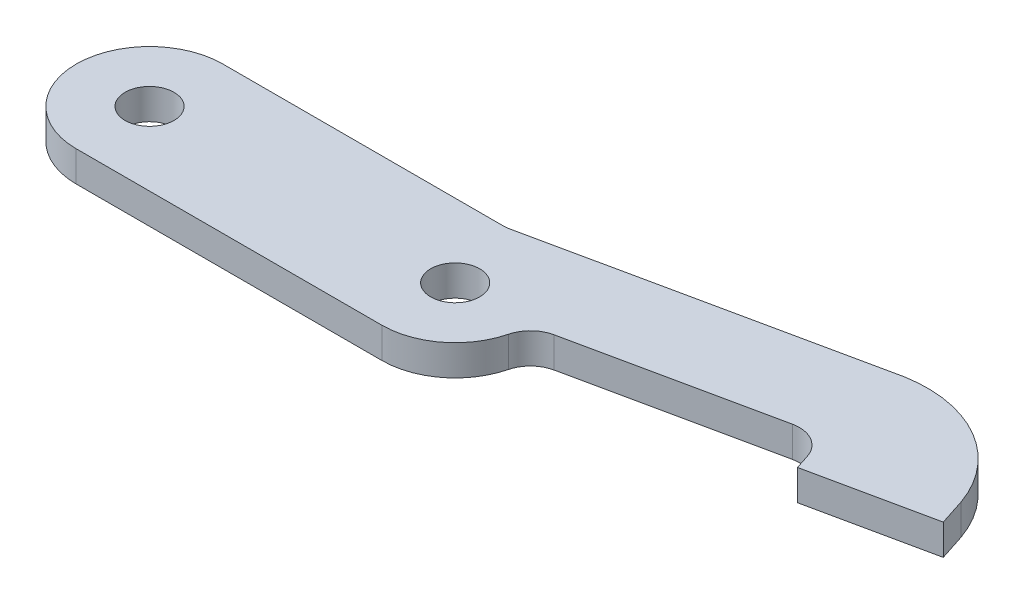
SolidWorks part; units mm, degrees
ref_plane "Front Plane" through (0, 0, 0) normal (0, 0, 1) x (1, 0, 0)
ref_plane "Top Plane" through (0, 0, 0) normal (0, 1, 0) x (1, 0, 0)
ref_plane "Right Plane" through (0, 0, 0) normal (1, 0, 0) x (0, 0, -1)
sketch "Sketch1" plane through (0, 0, 0) normal (0, 1, 0) x (1, 0, 0)
  line L0 (0, 12) -> (46.3095, 12)
  line L3 (0, -12) -> (50, -12)
  line L4 (62, 0) -> (102, 8.5023)
  line L5 (46.3095, 12) -> (100.1077, 23.4351)
  line L6 (122.4396, 10.3048) -> (123.8266, 6.0238)
  line L7 (146.0527, 1.8431) -> (104.1576, 1.8431) construction
  line L8 (104.1576, 1.8431) -> (102, 8.5023)
  line L9 (50, 0) -> (91.7136, 0) construction
  line L10 (104.1576, 1.8431) -> (123.8266, 6.0238)
  circle A0 centre (0, 0) radius 4
  circle A1 centre (50, 0) radius 4
  arc A2 (0, 12) -> (0, -12) centre (0, 0) ccw
  arc A3 (50, -12) -> (62, 0) centre (50, 0) ccw
  arc A5 (122.4396, 10.3048) -> (100.1077, 23.4351) centre (103.5499, 3.7336) ccw
  dimension "D1" = 8
  dimension "D2" = 24
  dimension "D10" = 20
  dimension "D3" = 50
  dimension "D4" = 15
  dimension "D5" = 4.5
  dimension "D6" = 20
  dimension "D7" = 40
  dimension "D8" = 12
  dimension "D9" = 12
  dimension "D11" = 55
  dimension "D12" = 7
extrude "Boss-Extrude1" add sketch "Sketch1" along normal blind 5
fillet "Fillet1" radius 5 3 edges at (62, 2.5, 0) (102, 2.5, -8.5023) (46.3095, 2.5, -12)
